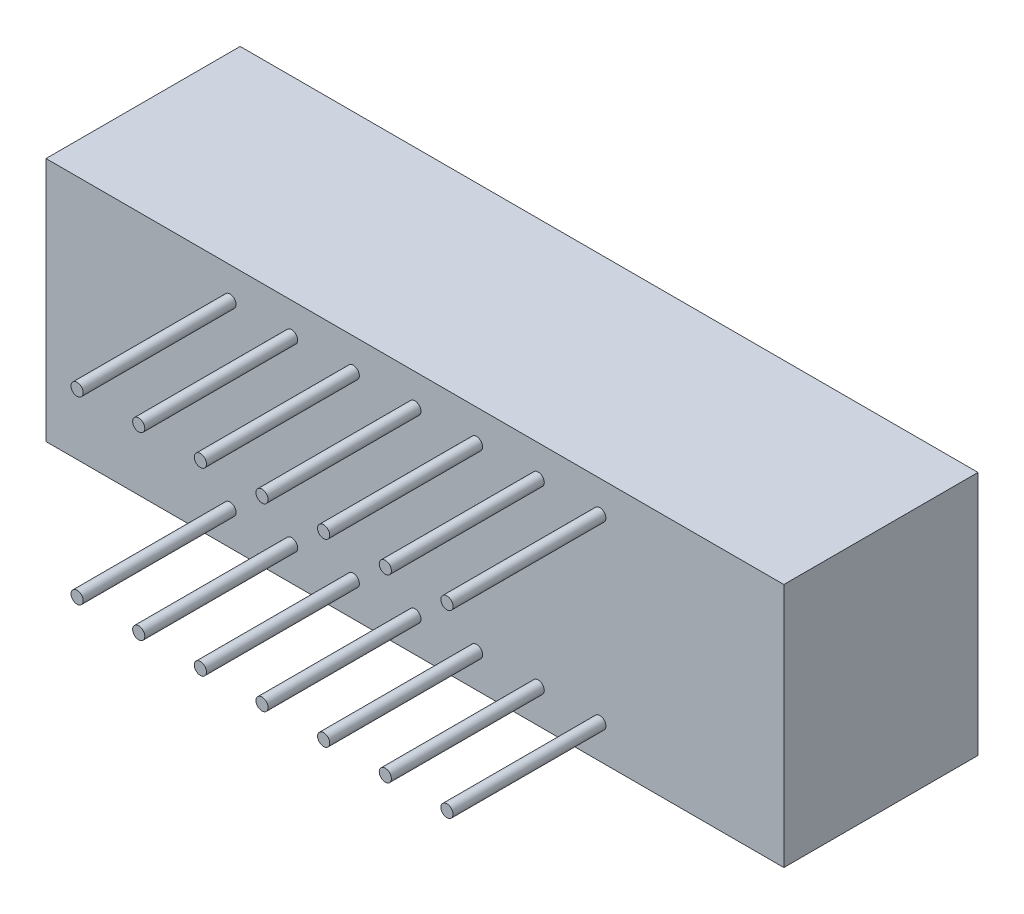
SolidWorks part; units mm, degrees
material "Neutron Star"
ref_plane "Front Plane" through (0, 0, 0) normal (0, 0, 1) x (1, 0, 0)
ref_plane "Top Plane" through (0, 0, 0) normal (0, 1, 0) x (1, 0, 0)
ref_plane "Right Plane" through (0, 0, 0) normal (1, 0, 0) x (0, 0, -1)
sketch "Sketch2" plane through (0, 0, 0) normal (0, 0, 1) x (1, 0, 0)
  line L1 (0, 0) -> (30.4, 0)
  line L2 (0, 0) -> (0, 10.1)
  line L3 (0, 10.1) -> (30.4, 10.1)
  line L4 (30.4, 0) -> (30.4, 10.1)
  dimension "D1" = 10.1
  dimension "D2" = 30.4
extrude "Boss-Extrude1" add sketch "Sketch2" along normal blind 8
sketch "Sketch3" plane through (0, 0, 8) normal (0, 0, 1) x (1, 0, 0)
  line L0 (30.4, 10.1) -> (0, 10.1) construction
  line L1 (0, 10.1) -> (0, 0) construction
  circle A0 centre (7.58, 8.805) radius 0.25
  circle A1 centre (10.12, 8.805) radius 0.25
  circle A2 centre (12.66, 8.805) radius 0.25
  circle A3 centre (15.2, 8.805) radius 0.25
  circle A4 centre (17.74, 8.805) radius 0.25
  circle A5 centre (20.28, 8.805) radius 0.25
  circle A6 centre (22.82, 8.805) radius 0.25
  circle A7 centre (10.12, 1.385) radius 0.25
  circle A8 centre (12.66, 1.385) radius 0.25
  circle A9 centre (15.2, 1.385) radius 0.25
  circle A10 centre (17.74, 1.385) radius 0.25
  circle A11 centre (20.28, 1.385) radius 0.25
  circle A12 centre (22.82, 1.385) radius 0.25
  circle A13 centre (7.58, 1.385) radius 0.25
  dimension "D1" = 0.5
  dimension "D2" = 1.295
  dimension "D3" = 7.58
  dimension "D4" = 7
  dimension "D5" = 2
extrude "Boss-Extrude2" add sketch "Sketch3" along normal blind 6.3
